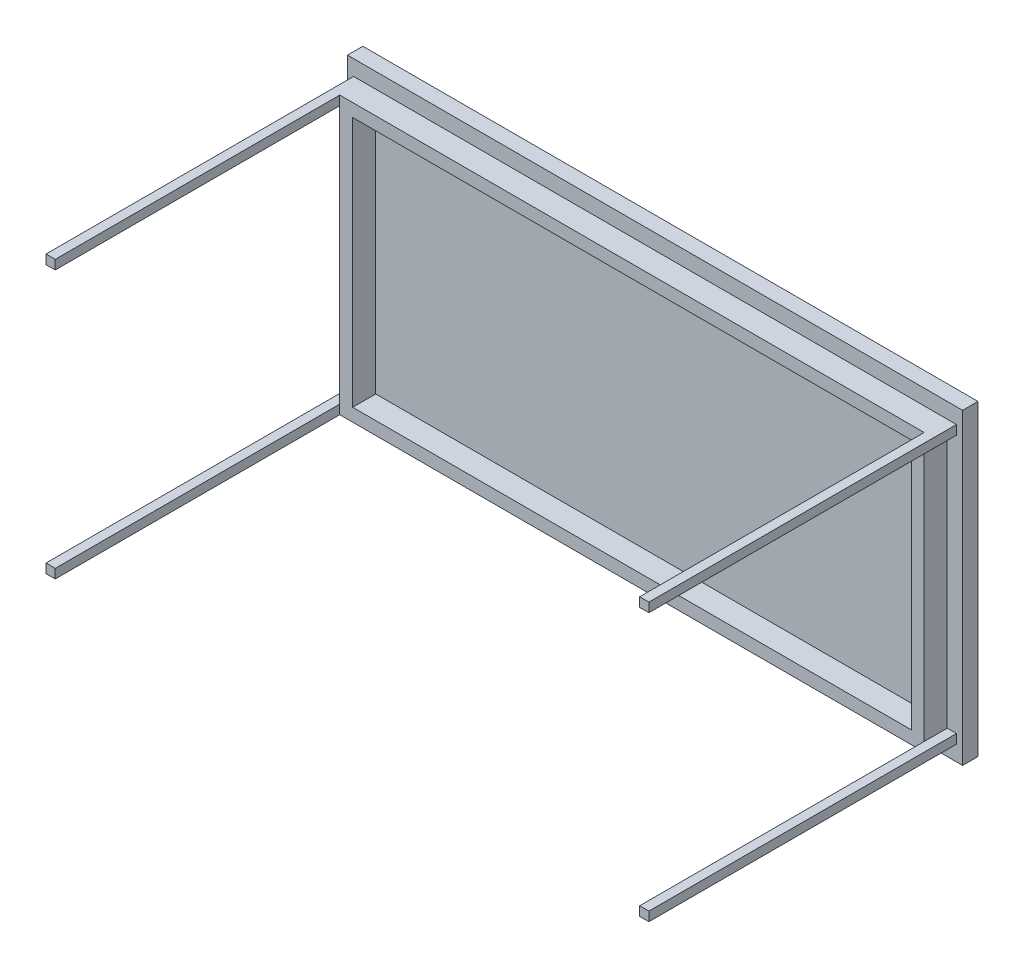
SolidWorks part; units mm, degrees
ref_plane "Plan de face" through (0, 0, 0) normal (0, 0, 1) x (1, 0, 0)
ref_plane "Plan de dessus" through (0, 0, 0) normal (0, 1, 0) x (1, 0, 0)
ref_plane "Plan de droite" through (0, 0, 0) normal (1, 0, 0) x (0, 0, -1)
sketch "Esquisse1" plane through (0, 0, 0) normal (0, 0, 1) x (1, 0, 0)
  line L1 (-1000, 500) -> (1000, 500)
  line L2 (-1000, 500) -> (-1000, -500)
  line L3 (-1000, -500) -> (1000, -500)
  line L4 (1000, 500) -> (1000, -500)
  line L5 (-1000, 500) -> (1000, -500) construction
  line L6 (-1000, -500) -> (1000, 500) construction
  point P0 (0, 0)
  dimension "D1" = 2000
  dimension "D2" = 1000
extrude "Boss.-Extru.1" add sketch "Esquisse1" along normal blind 50
sketch "Esquisse2" plane through (0, 0, 50) normal (0, 0, 1) x (1, 0, 0)
  line L4 (908, -408) -> (908, 408)
  line L5 (908, 408) -> (-908, 408)
  line L6 (-908, 408) -> (-908, -408)
  line L7 (-908, -408) -> (908, -408)
  line L8 (950, -450) -> (950, 450)
  line L9 (950, 450) -> (-950, 450)
  line L10 (-950, 450) -> (-950, -450)
  line L11 (-950, -450) -> (950, -450)
  line L12 (950, -450) -> (950, 450)
  line L13 (950, 450) -> (-950, 450)
  line L14 (-950, 450) -> (-950, -450)
  line L15 (-950, -450) -> (950, -450)
  dimension "D1" = 50
  dimension "D2" = 42
extrude "Boss.-Extru.2" add sketch "Esquisse2" along normal blind 75
sketch "Esquisse3" plane through (0, 0, 50) normal (0, 0, 1) x (1, 0, 0)
  line L0 (-950, 450) -> (-980, 450)
  line L1 (-980, 450) -> (-980, 420)
  line L2 (-980, 420) -> (-950, 420)
  line L3 (-950, 450) -> (-950, -450) construction
  line L4 (-950, 420) -> (-950, 450)
  line L5 (0, 0) -> (0, 265.0639) construction
  line L6 (0, 265.0639) -> (0, 0) construction
  line L7 (0, 0) -> (235.6478, 0) construction
  line L8 (980, 420) -> (950, 420)
  line L9 (980, 450) -> (980, 420)
  line L10 (950, 450) -> (980, 450)
  line L11 (950, 420) -> (950, 450)
  line L12 (980, -450) -> (980, -420)
  line L13 (950, -450) -> (980, -450)
  line L14 (950, -420) -> (950, -450)
  line L15 (980, -420) -> (950, -420)
  line L16 (-980, -420) -> (-950, -420)
  line L17 (-980, -450) -> (-980, -420)
  line L18 (-950, -450) -> (-980, -450)
  line L19 (-950, -420) -> (-950, -450)
  dimension "D1" = 30
  dimension "D2" = 30
extrude "Boss.-Extru.3" add sketch "Esquisse3" along normal blind 1000
